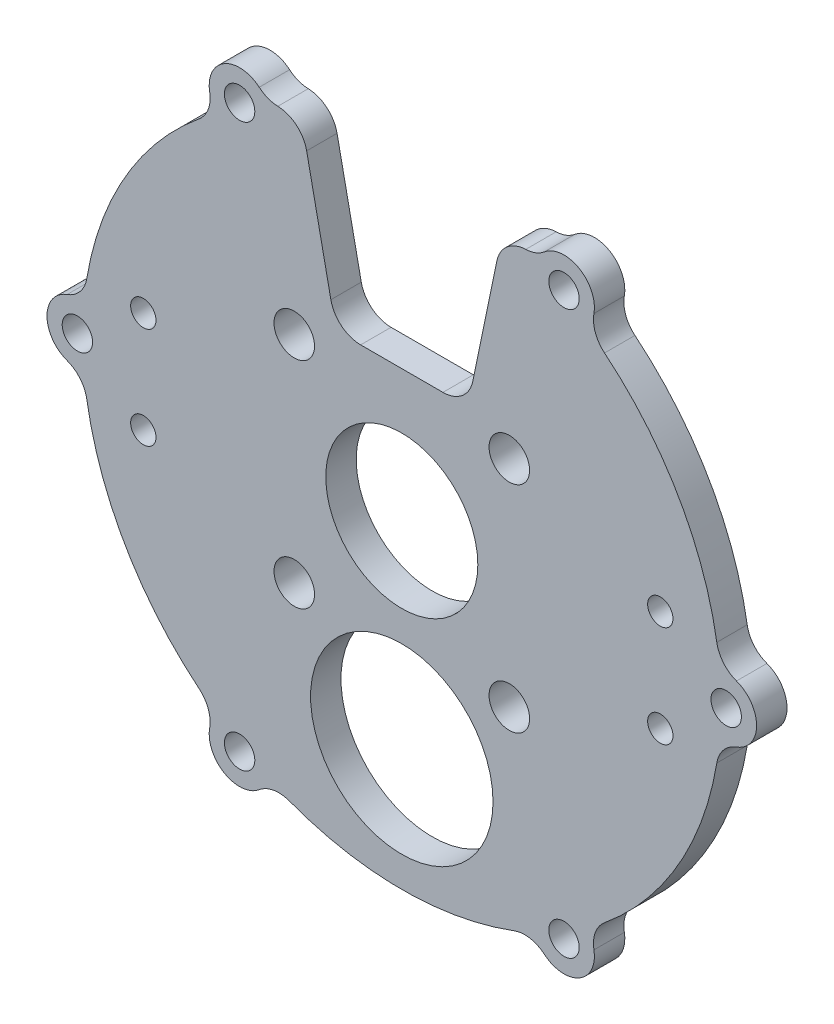
SolidWorks part; units mm, degrees
material "Thornel Mat VMA"
ref_plane "前视基准面" through (0, 0, 0) normal (0, 0, 1) x (1, 0, 0)
ref_plane "上视基准面" through (0, 0, 0) normal (0, 1, 0) x (1, 0, 0)
ref_plane "右视基准面" through (0, 0, 0) normal (1, 0, 0) x (0, 0, -1)
sketch "草图1" plane through (0, 0, 0) normal (0, 0, 1) x (1, 0, 0)
  line L0 (-10, 29.8706) -> (-6.5, 13)
  line L1 (10.6066, 10.6066) -> (-10.6066, 10.6066) construction
  line L2 (-10.6066, 10.6066) -> (-10.6066, -10.6066) construction
  line L3 (-10.6066, -10.6066) -> (10.6066, -10.6066) construction
  line L4 (10.6066, -10.6066) -> (10.6066, 10.6066) construction
  line L5 (-6.5, 13) -> (6.5, 13)
  line L6 (6.5, 13) -> (10, 29.8706)
  line L12 (-16, 27.7128) -> (-32, 0) construction
  line L13 (-32, 0) -> (-16, -27.7128) construction
  line L14 (-16, -27.7128) -> (16, -27.7128) construction
  line L15 (16, -27.7128) -> (32, 0) construction
  line L16 (32, 0) -> (16, 27.7128) construction
  line L17 (16, 27.7128) -> (-16, 27.7128) construction
  line L18 (-25.5, 5) -> (25.5, 5) construction
  line L19 (-25.5, 5) -> (-25.5, -5) construction
  line L20 (-25.5, -5) -> (25.5, -5) construction
  line L21 (25.5, 5) -> (25.5, -5) construction
  arc A0 (-10, 29.8706) -> (-13.1428, 28.6272) centre (0, 0) ccw
  circle A2 centre (0, 0) radius 15 construction
  circle A3 centre (-10.6066, 10.6066) radius 2
  circle A4 centre (-10.6066, -10.6066) radius 2
  circle A5 centre (10.6066, -10.6066) radius 2
  circle A6 centre (10.6066, 10.6066) radius 2
  circle A7 centre (0, 0) radius 7.5
  circle A9 centre (-25.5, 5) radius 1.25
  circle A14 centre (0, 0) radius 32 construction
  circle A15 centre (-16, 27.7128) radius 1.5
  circle A16 centre (16, 27.7128) radius 1.5
  circle A17 centre (32, 0) radius 1.5
  circle A18 centre (-32, 0) radius 1.5
  circle A19 centre (-16, -27.7128) radius 1.5
  circle A20 centre (16, -27.7128) radius 1.5
  arc A21 (-13.1428, 28.6272) -> (-18.2205, 25.6956) centre (-16, 27.7128) ccw
  arc A22 (18.2205, 25.6956) -> (13.1428, 28.6272) centre (16, 27.7128) ccw
  arc A23 (31.3633, -2.9317) -> (31.3633, 2.9317) centre (32, 0) ccw
  arc A24 (13.1428, -28.6272) -> (18.2205, -25.6956) centre (16, -27.7128) ccw
  arc A25 (-18.2205, -25.6956) -> (-13.1428, -28.6272) centre (-16, -27.7128) ccw
  arc A26 (-31.3633, 2.9317) -> (-31.3633, -2.9317) centre (-32, 0) ccw
  arc A27 (-18.2205, 25.6956) -> (-31.3633, 2.9317) centre (0, 0) ccw
  arc A28 (13.1428, 28.6272) -> (10, 29.8706) centre (0, 0) ccw
  arc A29 (31.3633, 2.9317) -> (18.2205, 25.6956) centre (0, 0) ccw
  arc A30 (18.2205, -25.6956) -> (31.3633, -2.9317) centre (0, 0) ccw
  circle A31 centre (-25.5, -5) radius 1.25
  arc A32 (-31.3633, -2.9317) -> (-18.2205, -25.6956) centre (0, 0) ccw
  arc A33 (-13.1428, -28.6272) -> (13.1428, -28.6272) centre (0, 0) ccw
  circle A34 centre (25.5, -5) radius 1.25
  circle A35 centre (25.5, 5) radius 1.25
  point P1 (0, 13)
  point P21 (-25.5, 0)
  point P22 (0, 5)
  dimension "D1" = 63
  dimension "D2" = 30
  dimension "D3" = 4
  dimension "D4" = 15
  dimension "D7" = 10
  dimension "D8" = 51
  dimension "D9" = 64
  dimension "D10" = 3
  dimension "D12" = 6
  dimension "D13" = 2.5
  dimension "D5" = 13
  dimension "D6" = 13
  dimension "D11" = 20
extrude "凸台-拉伸1" add sketch "草图1" along normal blind 3
sketch "草图2" plane through (0, 0, 3) normal (0, 0, 1) x (1, 0, 0)
  line L0 (0, 0) -> (0, 22.5816) construction
  circle A1 centre (0, -19.5) radius 9
  dimension "D4" = 18
  dimension "D1" = 19.5
extrude "切除-拉伸1" cut sketch "草图2" against normal through all
fillet "圆角1" radius 3 12 edges at (13.1428, 28.6272, 1.5) (18.2205, 25.6956, 1.5) (31.3633, 2.9317, 1.5) (31.3633, -2.9317, 1.5) (18.2205, -25.6956, 1.5) (13.1428, -28.6272, 1.5) (-13.1428, -28.6272, 1.5) (-18.2205, -25.6956, 1.5) (-31.3633, -2.9317, 1.5) (-18.2205, 25.6956, 1.5) (-13.1428, 28.6272, 1.5) (-31.3633, 2.9317, 1.5)
fillet "圆角2" radius 3 4 edges at (10, 29.8706, 1.5) (-10, 29.8706, 1.5) (6.5, 13, 1.5) (-6.5, 13, 1.5)
